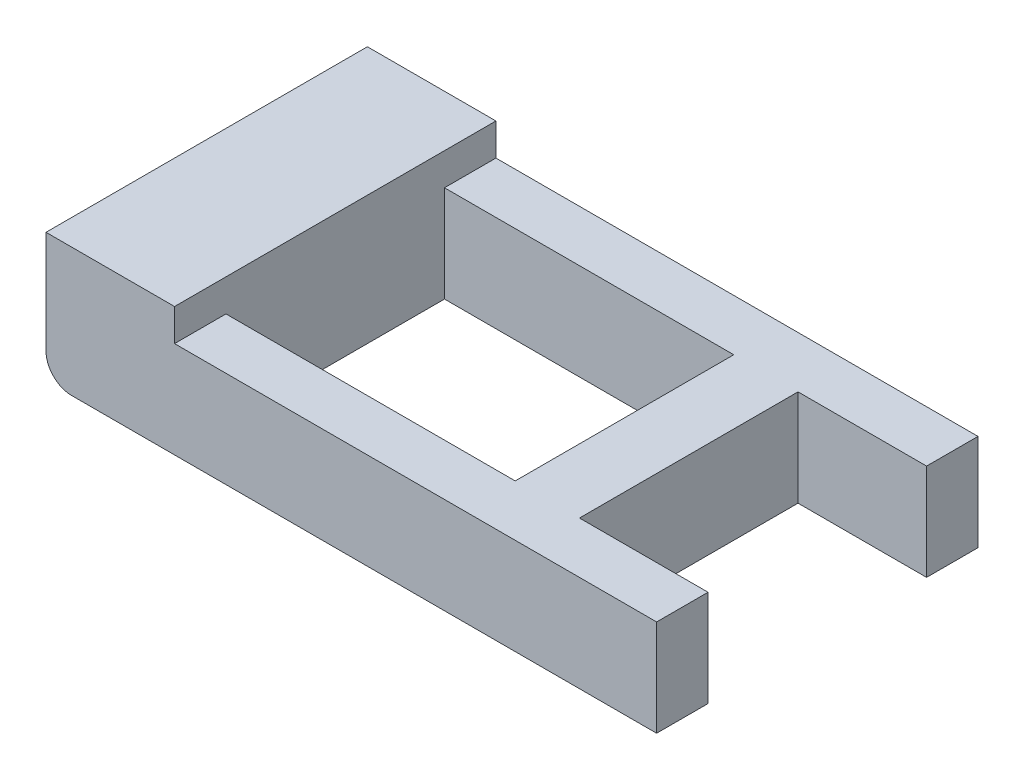
SolidWorks part; units mm, degrees
ref_plane "前视基准面" through (0, 0, 0) normal (0, 0, 1) x (1, 0, 0)
ref_plane "上视基准面" through (0, 0, 0) normal (0, 1, 0) x (1, 0, 0)
ref_plane "右视基准面" through (0, 0, 0) normal (1, 0, 0) x (0, 0, -1)
other "Configuration Table"
sketch "草图1" plane through (0, 0, 0) normal (0, 0, 1) x (1, 0, 0)
  line L1 (4, 0) -> (20, 0)
  line L2 (0, 4) -> (0, 20)
  line L3 (0, 20) -> (20, 20)
  line L4 (20, 0) -> (20, 20)
  arc A0 (4, 0) -> (0, 4) centre (4, 4) cw
  point P7 (0, 0)
  dimension "D3" = 4
  dimension "D1" = 20
  dimension "D2" = 20
extrude "凸台-拉伸1" add sketch "草图1" along normal blind 50
sketch "草图2" plane through (0, 0, 0) normal (-1, 0, 0) x (0, 0, 1)
  line L0 (3, 12.85) -> (13, 12.85) construction
  line L1 (3, 15.5) -> (13, 15.5)
  line L2 (3, 10.2) -> (13, 10.2)
  line L3 (23, 12.85) -> (33, 12.85) construction
  line L4 (23, 15.5) -> (33, 15.5)
  line L5 (23, 10.2) -> (33, 10.2)
  line L6 (41, 12.85) -> (46, 12.85) construction
  line L7 (41, 15.5) -> (46, 15.5)
  line L8 (41, 10.2) -> (46, 10.2)
  line L9 (50, 20) -> (0, 20) construction
  line L10 (0, 20) -> (0, 4) construction
  arc A0 (3, 15.5) -> (3, 10.2) centre (3, 12.85) ccw
  arc A1 (13, 10.2) -> (13, 15.5) centre (13, 12.85) ccw
  arc A2 (23, 15.5) -> (23, 10.2) centre (23, 12.85) ccw
  arc A3 (33, 10.2) -> (33, 15.5) centre (33, 12.85) ccw
  arc A4 (41, 15.5) -> (41, 10.2) centre (41, 12.85) ccw
  arc A5 (46, 10.2) -> (46, 15.5) centre (46, 12.85) ccw
  point P2 (8, 12.85)
  point P7 (28, 12.85)
  point P14 (43.5, 12.85)
  dimension "D1" = 5.3
  dimension "D2" = 4.5
  dimension "D3" = 5.3
  dimension "D4" = 5.3
  dimension "D5" = 10
  dimension "D6" = 10
  dimension "D7" = 10
  dimension "D8" = 5
  dimension "D9" = 8
  dimension "D10" = 3
extrude "切除-拉伸1" cut sketch "草图2" against normal blind 10
sketch "草图3" plane through (0, 0, 0) normal (0, -1, 0) x (1, 0, 0)
  line L0 (12.85, 46) -> (12.85, 29) construction
  line L1 (15.5, 46) -> (15.5, 29)
  line L2 (10.2, 46) -> (10.2, 29)
  line L3 (12.85, 20) -> (12.85, 5) construction
  line L4 (15.5, 20) -> (15.5, 5)
  line L5 (10.2, 20) -> (10.2, 5)
  line L7 (20, 50) -> (20, 0) construction
  line L8 (4, 50) -> (20, 50) construction
  line L9 (4, 0) -> (20, 0) construction
  arc A0 (15.5, 46) -> (10.2, 46) centre (12.85, 46) ccw
  arc A1 (10.2, 29) -> (15.5, 29) centre (12.85, 29) ccw
  arc A2 (15.5, 20) -> (10.2, 20) centre (12.85, 20) ccw
  arc A3 (10.2, 5) -> (15.5, 5) centre (12.85, 5) ccw
  point P2 (12.85, 37.5)
  point P7 (12.85, 12.5)
  dimension "D1" = 17
  dimension "D2" = 15
  dimension "D3" = 4.5
  dimension "D4" = 5.3
  dimension "D5" = 5.3
  dimension "D6" = 4
  dimension "D7" = 5
extrude "切除-拉伸2" cut sketch "草图3" against normal blind 10
sketch "草图4" plane through (0, 0, 0) normal (0, -1, 0) x (1, 0, 0)
  line L0 (95, 50) -> (95, 42)
  line L1 (0, 50) -> (0, 0) construction
  line L2 (20, 50) -> (95, 50)
  line L4 (95, 0) -> (20, 0)
  line L5 (20, 42) -> (20, 50)
  line L6 (20, 42) -> (65, 42)
  line L7 (20, 50) -> (20, 0) construction
  line L8 (95, 8) -> (75, 8)
  line L10 (75, 42) -> (75, 8)
  line L12 (65, 42) -> (65, 8)
  line L13 (75, 42) -> (95, 42)
  line L14 (65, 8) -> (20, 8)
  line L15 (95, 8) -> (95, 0)
  line L16 (20, 50) -> (20, 42)
  line L17 (20, 8) -> (20, 0)
  line M18 (20, 0) -> (20, 50)
  dimension "D1" = 95
  dimension "D2" = 8
  dimension "D3" = 8
  dimension "D4" = 30
  dimension "D5" = 55
extrude "凸台-拉伸2" add sketch "草图4" against normal blind 15 contours L15 L8 L10 L13 L0 L2 L6 L12 L14 L4 M18
